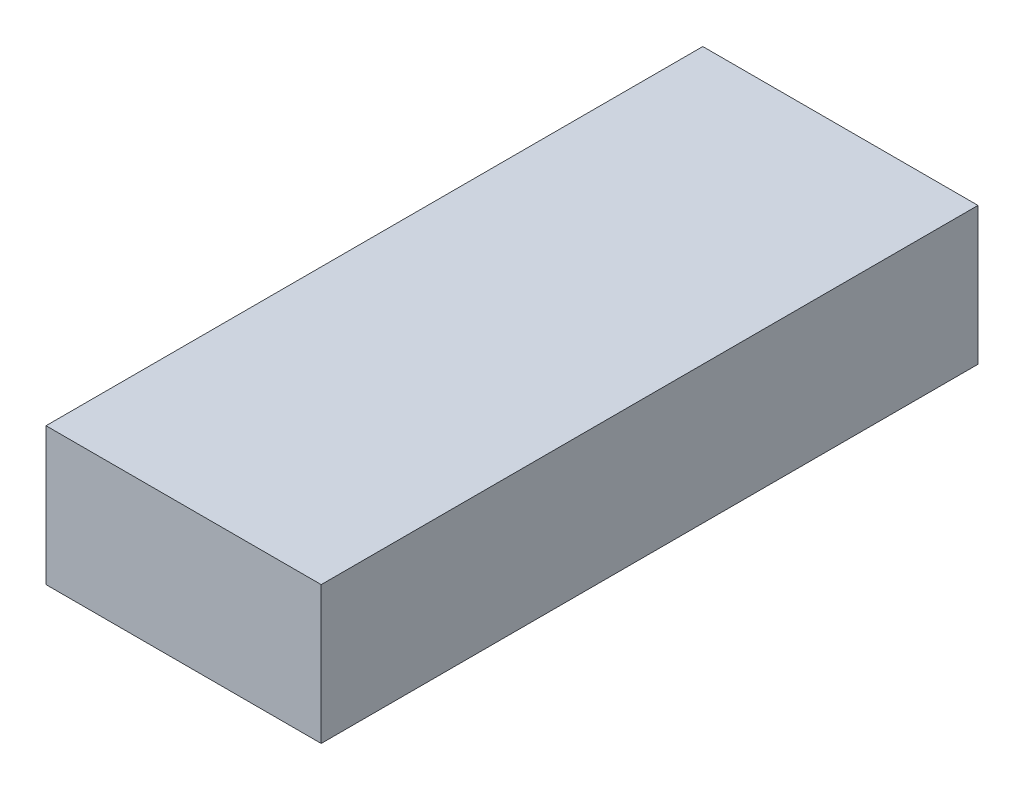
SolidWorks part; units mm, degrees
ref_plane "Front Plane" through (0, 0, 0) normal (0, 0, 1) x (1, 0, 0)
ref_plane "Top Plane" through (0, 0, 0) normal (0, 1, 0) x (1, 0, 0)
ref_plane "Right Plane" through (0, 0, 0) normal (1, 0, 0) x (0, 0, -1)
sketch "Sketch1" plane through (0, 0, 0) normal (0, 0, 1) x (1, 0, 0)
  line L1 (-30, -15) -> (30, -15)
  line L2 (-30, -15) -> (-30, 15)
  line L3 (-30, 15) -> (30, 15)
  line L4 (30, -15) -> (30, 15)
  line L5 (-30, -15) -> (30, 15) construction
  line L6 (-30, 15) -> (30, -15) construction
  point P0 (0, 0)
  dimension "D1" = 60
  dimension "D2" = 30
extrude "Boss-Extrude1" add sketch "Sketch1" along normal mid plane 143.2001
